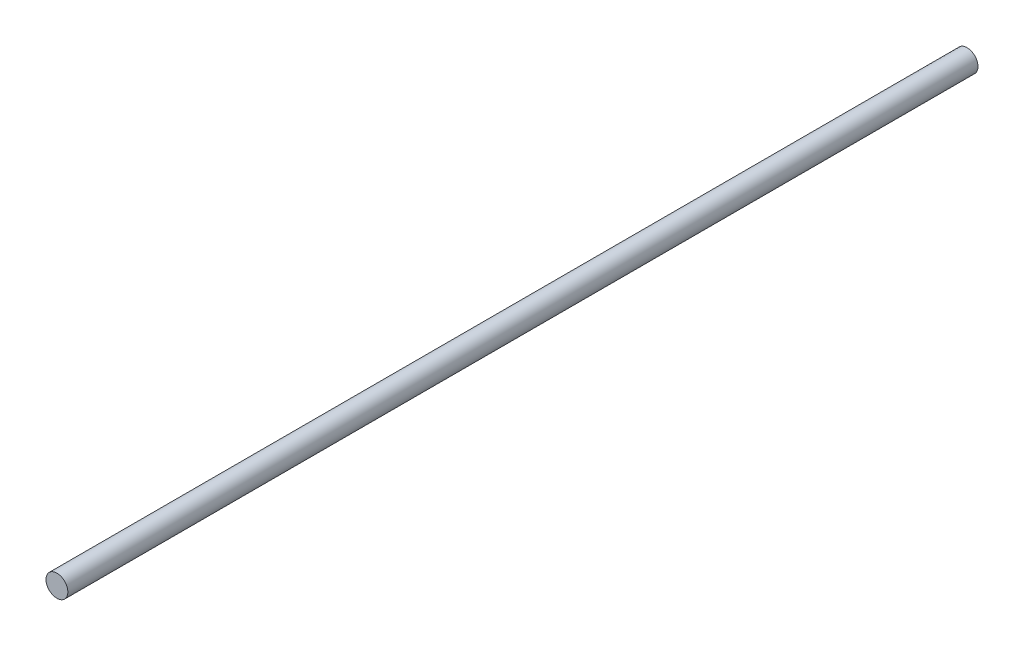
SolidWorks part; units mm, degrees
ref_plane "Спереди" through (0, 0, 0) normal (0, 0, 1) x (1, 0, 0)
ref_plane "Сверху" through (0, 0, 0) normal (0, 1, 0) x (1, 0, 0)
ref_plane "Справа" through (0, 0, 0) normal (1, 0, 0) x (0, 0, -1)
sketch "Эскиз1" plane through (0, 0, 0) normal (0, 0, 1) x (1, 0, 0)
  circle A0 centre (0, 0) radius 6
  dimension "D1" = 12
extrude "Бобышка-Вытянуть1" add sketch "Эскиз1" along normal blind 500
cosmetic thread "Условное изображение резьбы1" parameters "D2"=10
